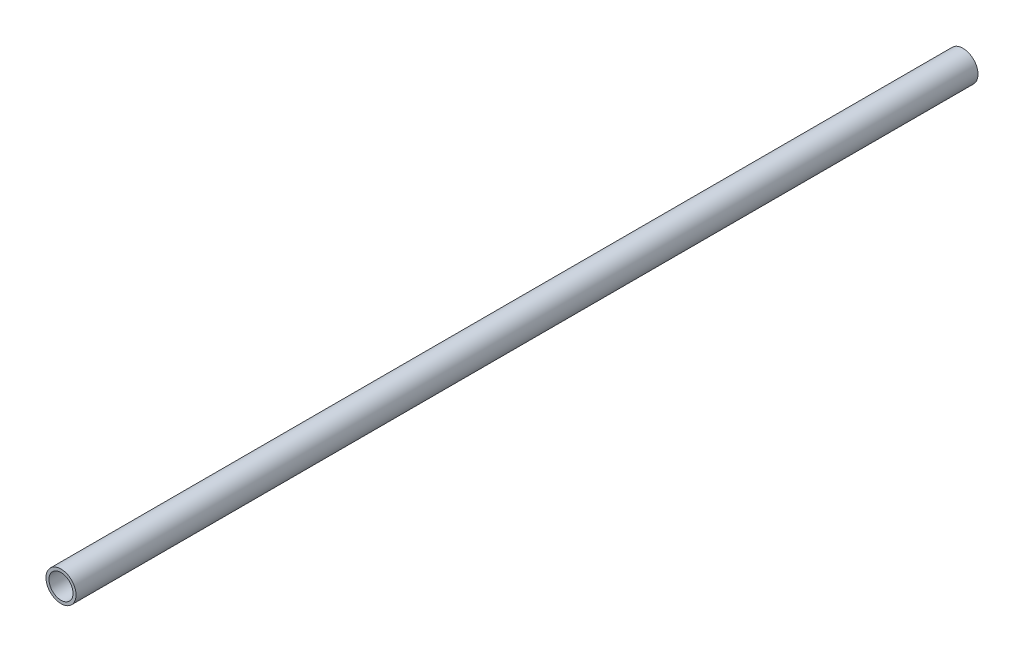
SolidWorks part; units mm, degrees
material "Thornel VCB-20 ｶｰﾎﾞﾝ ｸﾛｽ"
ref_plane "正面" through (0, 0, 0) normal (0, 0, 1) x (1, 0, 0)
ref_plane "平面" through (0, 0, 0) normal (0, 1, 0) x (1, 0, 0)
ref_plane "右側面" through (0, 0, 0) normal (1, 0, 0) x (0, 0, -1)
sketch "ｽｹｯﾁ1" plane through (0, 0, 0) normal (0, 0, 1) x (1, 0, 0)
  circle A0 centre (0, 0) radius 5
  circle A1 centre (0, 0) radius 4
  dimension "D1" = 10
  dimension "D2" = 8
extrude "ﾎﾞｽ - 押し出し1" add sketch "ｽｹｯﾁ1" along normal blind 300
sketch "ｽｹｯﾁ2" plane through (0, 0, 0) normal (0, 1, 0) x (1, 0, 0)
  line L0 (0, 0) -> (0, -300) construction
  line L1 (-4, -300) -> (4, -300) construction
  point P5 (0, 0)
